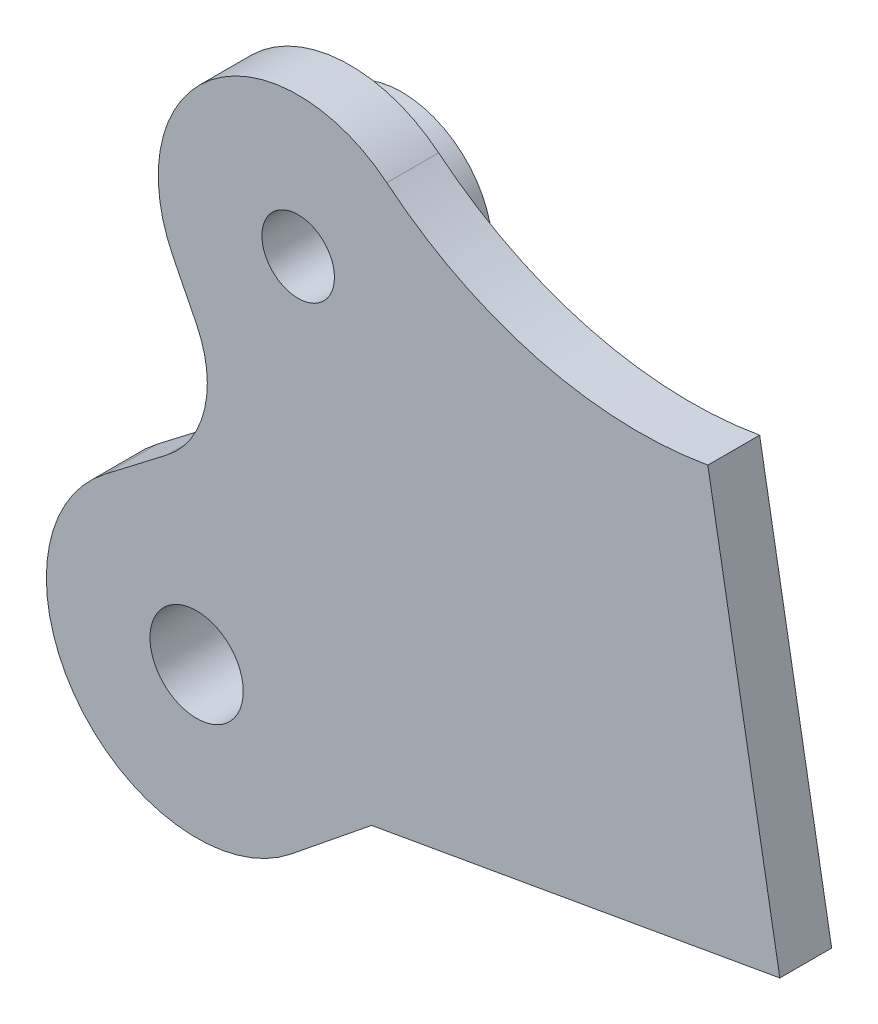
SolidWorks part; units mm, degrees
material "ABS"
ref_plane "Спереди" through (0, 0, 0) normal (0, 0, 1) x (1, 0, 0)
ref_plane "Сверху" through (0, 0, 0) normal (0, 1, 0) x (1, 0, 0)
ref_plane "Справа" through (0, 0, 0) normal (1, 0, 0) x (0, 0, -1)
sketch "Sketch1" plane through (0, 0, 0) normal (0, 0, 1) x (1, 0, 0)
  line L0 (-12.0689, -6.0492) -> (-9.8284, -10.5191)
  line L1 (-12.6807, -22.9335) -> (-18.6271, -27.4964)
  line L2 (-0.6913, -50.2819) -> (7.0893, -44)
  line L3 (7.0893, -44) -> (46.4817, -37.0541)
  line L4 (46.4817, -37.0541) -> (39.5357, 2.3382)
  line L5 (7.0893, -44) -> (51.1124, -44) construction
  line L6 (39.5357, 2.3382) -> (9.2302, -3.0054) construction
  circle A0 centre (0, 0) radius 3.5
  circle A1 centre (-9.8, -39) radius 4.5
  arc A2 (-18.6271, -27.4964) -> (-0.6913, -50.2819) centre (-9.8, -39) ccw
  arc A3 (8.5547, 10.4435) -> (-12.0689, -6.0492) centre (0, 0) ccw
  arc A4 (-12.6807, -22.9335) -> (-9.8284, -10.5191) centre (-18.7683, -15) ccw
  arc A5 (8.5547, 10.4435) -> (39.5357, 2.3382) centre (32.872, 40.1299) ccw
  dimension "D1" = 9
  dimension "D2" = 7
  dimension "D3" = 9.8
  dimension "D4" = 39
  dimension "D5" = 10
  dimension "D6" = 10
  dimension "D7" = 10
  dimension "D14" = 5
  dimension "D8" = 15
  dimension "D9" = 5
  dimension "D10" = 40
  dimension "D11" = 10
  dimension "D12" = 40
  dimension "D13" = 10
extrude "Boss-Extrude1" add sketch "Sketch1" against normal blind 5
sketch "Sketch2" plane through (0, 0, -5) normal (0, 0, -1) x (-1, 0, 0)
  circle A0 centre (0, 0) radius 8.75
  circle A1 centre (9.8, -39) radius 8.75
  circle A2 centre (0, 0) radius 3.5
  circle A3 centre (9.8, -39) radius 4.5
  dimension "D1" = 17.5
  dimension "D2" = 17.5
extrude "Boss-Extrude2" add sketch "Sketch2" along normal blind 5
